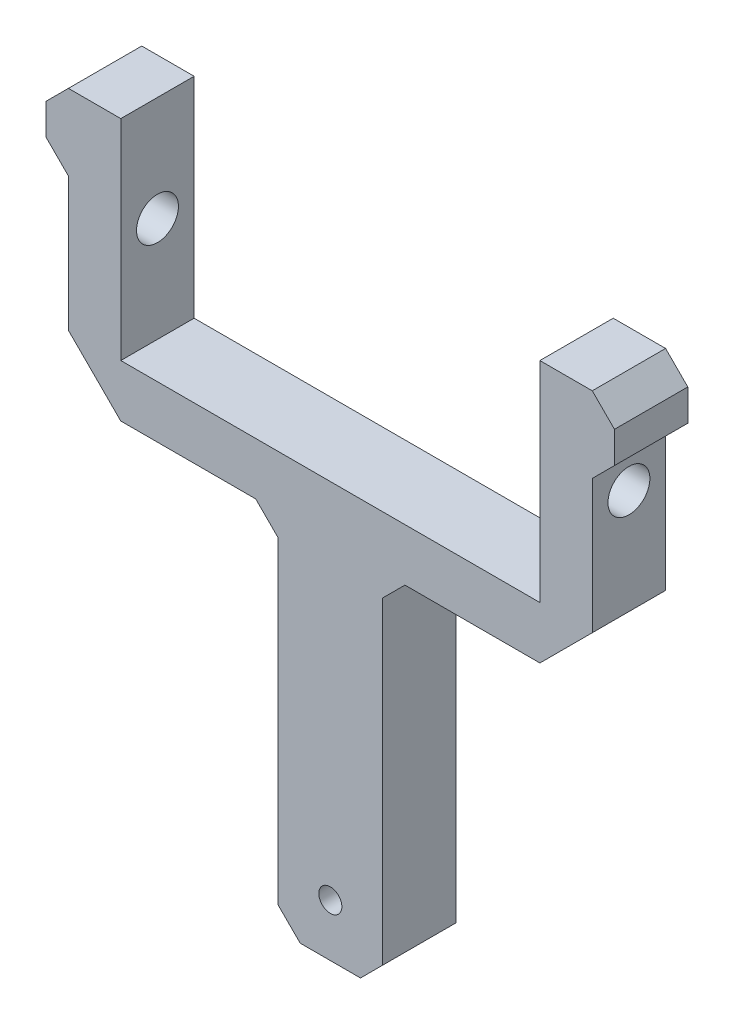
SolidWorks part; units mm, degrees
ref_plane "Alzado" through (0, 0, 0) normal (0, 0, 1) x (1, 0, 0)
ref_plane "Planta" through (0, 0, 0) normal (0, 1, 0) x (1, 0, 0)
ref_plane "Vista lateral" through (0, 0, 0) normal (1, 0, 0) x (0, 0, -1)
sketch "Croquis1" plane through (0, 0, 0) normal (0, 0, 1) x (1, 0, 0)
  line L0 (0, 0) -> (0, 44.6) construction
  line L1 (-5, 5) -> (5, 5)
  line L2 (-5, 5) -> (-5, -5)
  line L3 (-5, -5) -> (5, -5)
  line L4 (5, 5) -> (5, -5)
  line L5 (-5, 5) -> (5, -5) construction
  line L6 (-5, -5) -> (5, 5) construction
  line L7 (-20, 54.6) -> (-25, 54.6)
  line L8 (-20, 54.6) -> (20, 54.6)
  line L9 (-20, 54.6) -> (-20, 34.6)
  line L10 (-20, 34.6) -> (20, 34.6)
  line L12 (-20, 54.6) -> (20, 34.6) construction
  line L13 (-20, 34.6) -> (20, 54.6) construction
  line L18 (-25, 54.6) -> (-27.1213, 52.4787)
  line L19 (-27.1213, 52.4787) -> (-27.1213, 49.4787)
  line L20 (-27.1213, 49.4787) -> (-25, 47.3574)
  line L21 (-25, 47.3574) -> (-25, 34.5974)
  line L22 (20, 54.6) -> (20, 34.6)
  line L23 (-25, 34.5974) -> (-20.0026, 29.6)
  line L24 (-7.1213, 29.6) -> (-20.0026, 29.6)
  line L25 (-5, 27.4787) -> (-7.1213, 29.6)
  line L26 (-5, 5) -> (-5, 27.4787)
  line L27 (25, 47.3574) -> (25, 34.5974)
  line L28 (27.1213, 49.4787) -> (25, 47.3574)
  line L29 (25, 54.6) -> (27.1213, 52.4787)
  line L30 (27.1213, 52.4787) -> (27.1213, 49.4787)
  line L31 (20, 54.6) -> (25, 54.6)
  line L32 (25, 34.5974) -> (20.0026, 29.6)
  line L33 (7.1213, 29.6) -> (20.0026, 29.6)
  line L34 (5, 27.4787) -> (7.1213, 29.6)
  line L35 (5, 5) -> (5, 27.4787)
  circle A0 centre (0, 0) radius 1.1
  point P0 (0, 0)
  point P29 (-13.562, 29.6)
  dimension "D2" = 2.2
  dimension "D1" = 10
  dimension "D3" = 40
  dimension "D4" = 20
  dimension "D5" = 5
  dimension "D6" = 44.6
  dimension "D7" = 3
  dimension "D8" = 3
  dimension "D9" = 3
  dimension "D10" = 12.76
  dimension "D11" = 135
  dimension "D12" = 3
  dimension "D13" = 5
  dimension "D14" = 135
  dimension "D15" = 10
extrude "Saliente-Extruir1" add sketch "Croquis1" along normal blind 7
sketch "Croquis2" plane through (0, 0, 0) normal (0, 0, -1) x (-1, 0, 0)
  line L0 (-5, -5) -> (-2.8787, -5)
  line L1 (5, -5) -> (-5, -5) construction
  line L2 (-2.8787, -5) -> (-5, -2.8787)
  line L3 (-5, -5) -> (-5, 27.4787) construction
  line L4 (-5, -2.8787) -> (-5, -5)
  line L5 (0, 55) -> (0, -55) construction
  line L6 (2.8787, -5) -> (5, -2.8787)
  line L7 (5, -5) -> (2.8787, -5)
  line L8 (5, -2.8787) -> (5, -5)
  dimension "D1" = 45
  dimension "D2" = 3
extrude "Cortar-Extruir1" cut sketch "Croquis2" against normal through all
sketch "Croquis3" plane through (-25, 0, 0) normal (-1, 0, 0) x (0, 0, 1)
  line L0 (3.5, 34.5974) -> (3.5, 44.5974) construction
  line L1 (7, 34.5974) -> (0, 34.5974) construction
  circle A0 centre (3.5, 44.5974) radius 2
  dimension "D1" = 4
extrude "Cortar-Extruir3" cut sketch "Croquis3" against normal through all
sketch "Croquis4" plane through (-25, 0, 0) normal (-1, 0, 0) x (0, 0, 1)
  circle A0 centre (3.5, 44.5974) radius 3.75
  dimension "D1" = 7.5
extrude "Cortar-Extruir4" cut sketch "Croquis4" along normal through all
sketch "Croquis5" plane through (25, 0, 0) normal (1, 0, 0) x (0, 0, -1)
  circle A0 centre (-3.5, 44.5974) radius 3.75
extrude "Cortar-Extruir5" cut sketch "Croquis5" along normal through all
